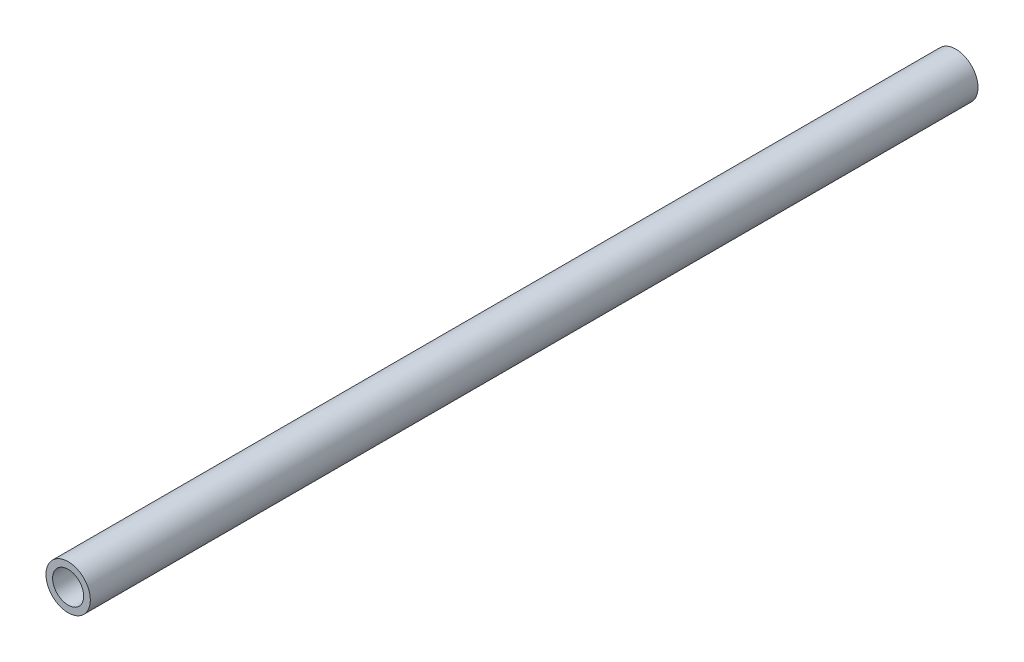
SolidWorks part; units mm, degrees
ref_plane "Front Plane" through (0, 0, 0) normal (0, 0, 1) x (1, 0, 0)
ref_plane "Top Plane" through (0, 0, 0) normal (0, 1, 0) x (1, 0, 0)
ref_plane "Right Plane" through (0, 0, 0) normal (1, 0, 0) x (0, 0, -1)
sketch "Sketch1" plane through (0, 0, 0) normal (0, 0, 1) x (1, 0, 0)
  circle A0 centre (0, 0) radius 5
  circle A1 centre (0, 0) radius 3.5
  dimension "D1" = 10
  dimension "D2" = 7
extrude "Boss-Extrude1" add sketch "Sketch1" along normal blind 200
